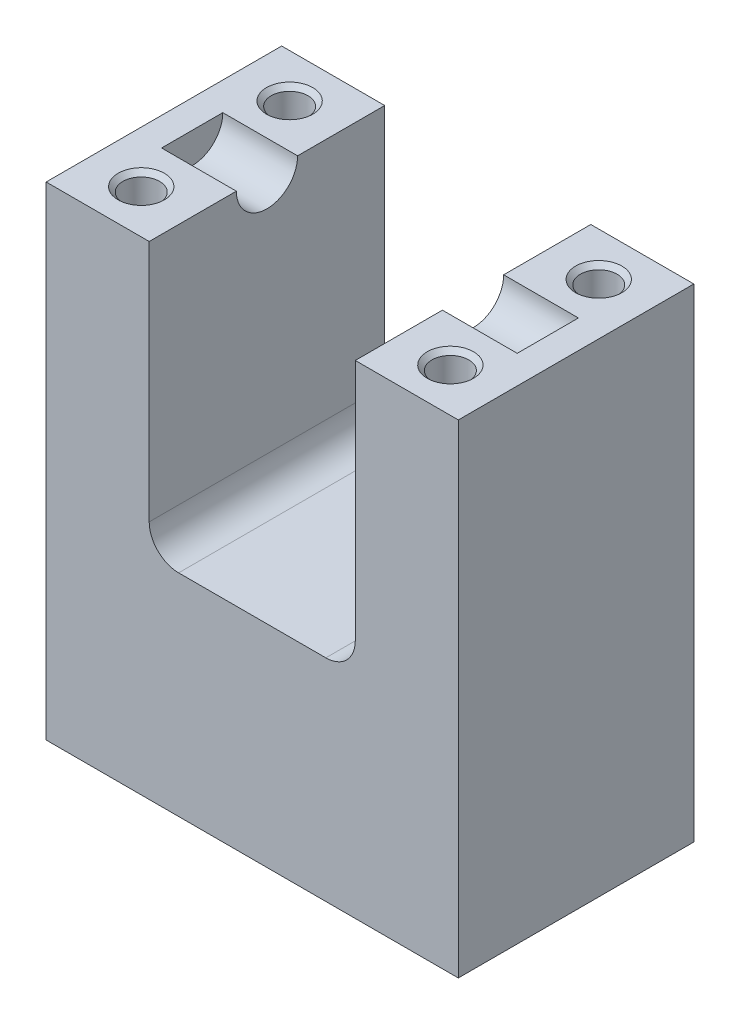
SolidWorks part; units mm, degrees
ref_plane "Front Plane" through (0, 0, 0) normal (0, 0, 1) x (1, 0, 0)
ref_plane "Top Plane" through (0, 0, 0) normal (0, 1, 0) x (1, 0, 0)
ref_plane "Right Plane" through (0, 0, 0) normal (1, 0, 0) x (0, 0, -1)
sketch "Sketch1" plane through (0, 0, 0) normal (0, 1, 0) x (1, 0, 0)
  line L0 (0, 0) -> (44.45, 0)
  line L1 (44.45, 0) -> (44.45, 25.4)
  line L2 (44.45, 25.4) -> (20.066, 25.4)
  line L3 (20.066, 25.4) -> (20.066, 39.116)
  line L4 (20.066, 39.116) -> (0, 39.116)
  line L5 (0, 39.116) -> (0, 0)
  dimension "D1" = 39.116
  dimension "D2" = 44.45
  dimension "D3" = 20.066
  dimension "D4" = 25.4
extrude "L-Base" add sketch "Sketch1" along normal blind 12.7
sketch "Sketch3" plane through (0, 12.7, 0) normal (0, 1, 0) x (1, 0, 0)
  line L1 (0, 0) -> (44.45, 0)
  line L2 (0, 0) -> (0, 25.4)
  line L3 (0, 25.4) -> (44.45, 25.4)
  line L4 (44.45, 0) -> (44.45, 25.4)
  line L5 (0, 0) -> (44.45, 25.4) construction
  line L6 (0, 25.4) -> (44.45, 0) construction
  point P5 (22.225, 12.7)
extrude "Rectangular Extrude" add sketch "Sketch3" along normal offset from surface (10.5664 mm away) 23.2664 up to face at (21.5053, 0, -21.5053)
sketch "Sketch4" plane through (0, 23.2664, 0) normal (0, 1, 0) x (1, 0, 0)
  line L0 (20.066, 25.4) -> (0, 25.4) construction
  line L1 (0, 0) -> (11.1125, 0)
  line L2 (0, 0) -> (0, 25.4)
  line L3 (0, 25.4) -> (11.1125, 25.4)
  line L4 (11.1125, 0) -> (11.1125, 25.4)
  line L5 (0, 0) -> (11.1125, 25.4) construction
  line L6 (0, 25.4) -> (11.1125, 0) construction
  line L7 (44.45, 25.4) -> (0, 25.4) construction
  line L8 (44.45, 0) -> (33.3375, 0)
  line L9 (44.45, 0) -> (44.45, 25.4)
  line L10 (44.45, 25.4) -> (33.3375, 25.4)
  line L11 (33.3375, 0) -> (33.3375, 25.4)
  line L12 (44.45, 0) -> (33.3375, 25.4) construction
  line L13 (44.45, 25.4) -> (33.3375, 0) construction
  line L14 (22.225, 0) -> (22.225, 25.4) construction
  line L15 (0, 0) -> (44.45, 0) construction
  point P4 (5.5563, 12.7)
  point P12 (38.8937, 12.7)
  dimension "D1" = 11.1125
  dimension "D2" = 11.1125
extrude "Fork Extrude" add sketch "Sketch4" along normal blind 29.3624
sketch "Sketch6" plane through (0, 52.6288, 0) normal (0, 1, 0) x (1, 0, 0)
  line L0 (0, 12.7) -> (44.45, 12.7) construction
  line L1 (0, 25.4) -> (0, 0) construction
  line L2 (44.45, 0) -> (44.45, 25.4) construction
  line L3 (11.1125, 0) -> (11.1125, 25.4) construction
  line L4 (3.048, 12.7) -> (41.402, 12.7)
  line L5 (3.048, 12.7) -> (3.048, 9.398)
  line L6 (3.048, 9.398) -> (41.402, 9.398)
  line L7 (41.402, 12.7) -> (41.402, 9.398)
  line L8 (3.048, 12.7) -> (41.402, 9.398) construction
  line L9 (3.048, 9.398) -> (41.402, 12.7) construction
  line L10 (0, 0) -> (44.45, 0) construction
  line L11 (0, 0) -> (0, 25.4) construction
  line L12 (0, 25.4) -> (44.45, 25.4) construction
  line L13 (44.45, 0) -> (44.45, 25.4) construction
  line L14 (0, 0) -> (44.45, 25.4) construction
  line L15 (0, 25.4) -> (44.45, 0) construction
  point P10 (22.225, 12.7)
  dimension "D1" = 3.302
  dimension "D2" = 38.354
  dimension "D3" = 8.0645
revolve "Shaft Recess" cut sketch "Sketch6" angle 360 about L0
hole_wizard "#4 Expansion Insert Recesses #1" positions "Sketch8" profile "Sketch7" counterbore size "#4" standard "ANSI Inch"
sketch "Sketch8" plane through (0, 52.6288, 0) normal (0, 1, 0) x (1, 0, 0)
  line L0 (5.5562, 25.4) -> (5.5562, 0) construction
  line L1 (11.1125, 25.4) -> (0, 25.4) construction
  line L2 (0, 0) -> (11.1125, 0) construction
  line L4 (38.8937, 25.4) -> (38.8937, 0) construction
  line L5 (44.45, 25.4) -> (33.3375, 25.4) construction
  line L6 (33.3375, 0) -> (44.45, 0) construction
  line L8 (11.1125, 20.701) -> (0, 20.701) construction
  line L9 (11.1125, 16.002) -> (11.1125, 25.4) construction
  line L10 (0, 25.4) -> (0, 0) construction
  line L12 (11.1125, 4.699) -> (0, 4.699) construction
  line L13 (11.1125, 0) -> (11.1125, 9.398) construction
  line L15 (33.3375, 20.701) -> (44.45, 20.701) construction
  line L16 (33.3375, 25.4) -> (33.3375, 16.002) construction
  line L17 (44.45, 0) -> (44.45, 25.4) construction
  line L19 (33.3375, 4.699) -> (44.45, 4.699) construction
  line L20 (33.3375, 25.4) -> (33.3375, 0) construction
  point P0 (5.5562, 20.701)
  point P2 (5.5563, 4.699)
  point P4 (38.8937, 20.701)
  point P6 (38.8937, 4.699)
  dimension "D1" = 16.002
sketch "Sketch7" plane through (5.5562, 52.6288, -20.701) normal (1, 0, 0) x (0, 0, 1)
  line L0 (0, 0) -> (0, 13.6806)
  line L1 (0, 13.6806) -> (1.6319, 12.7)
  line L2 (1.6319, 12.7) -> (1.6319, 4.7625)
  line L3 (1.6319, 4.7625) -> (1.9844, 4.7625)
  line L4 (1.9844, 4.7625) -> (1.9844, 0)
  line L5 (1.9844, 0) -> (0, 0)
  line L10 (0, 13.6806) -> (-1.632, 12.7) construction
  line L11 (0, -6.35) -> (0, 107.95) construction
  dimension "Hole Dia." = 3.2639
  dimension "Hole Depth" = 12.7
  dimension "C'Bore Dia." = 3.9688
  dimension "C'Bore Depth" = 4.7625
  dimension "Drill Angle" = 118
hole_wizard "#4 Expansion Insert Recesses #2" positions "Sketch11" profile "Sketch10" counterbore size "#4" standard "ANSI Inch"
sketch "Sketch11" plane through (0, 0, 0) normal (0, -1, 0) x (-1, 0, 0)
  line L0 (0, 39.116) -> (0, 0) construction
  line L1 (0, 0) -> (-44.45, 0) construction
  point P0 (-10.033, 10.033)
  point P2 (-28.956, 10.033)
  point P4 (-10.033, 28.956)
  dimension "D1" = 10.033
  dimension "D2" = 10.033
  dimension "D3" = 18.923
  dimension "D4" = 18.923
sketch "Sketch10" plane through (10.033, 0, -10.033) normal (1, 0, 0) x (0, 0, -1)
  line L0 (0, 0) -> (0, 10.5056)
  line L1 (0, 10.5056) -> (1.6319, 9.525)
  line L2 (1.6319, 9.525) -> (1.6319, 4.7625)
  line L3 (1.6319, 4.7625) -> (1.9844, 4.7625)
  line L4 (1.9844, 4.7625) -> (1.9844, 0)
  line L5 (1.9844, 0) -> (0, 0)
  line L10 (0, 10.5056) -> (-1.632, 9.525) construction
  line L11 (0, -6.35) -> (0, 107.95) construction
  dimension "Hole Dia." = 3.2639
  dimension "Hole Depth" = 9.525
  dimension "C'Bore Dia." = 3.9688
  dimension "C'Bore Depth" = 4.7625
  dimension "Drill Angle" = 118
fillet "L-Base Fillet" radius 6.35 3 edges at (10.033, 12.7, -39.116)
fillet "Fork Fillet" radius 3.175 2 edges at (33.3375, 23.2664, -12.7)
chamfer "Installation Chamfers #1" distance 0.508 angle 45 4 edges at (38.8937, 52.6288, -18.7166) (38.8937, 52.6288, -2.7146) (5.5563, 52.6288, -2.7146) (5.5562, 52.6288, -18.7166)
chamfer "Installation Chamfers #2" distance 0.508 angle 45 3 edges at (10.033, 0, -30.9404) (10.033, 0, -12.0174) (28.956, 0, -12.0174)
chamfer "Print Bed Chamfer" distance 0.508 angle 45 7 edges at (0, 0, -19.558) (10.033, 0, -39.116) (20.066, 0, -35.433) (35.433, 0, -25.4) (44.45, 0, -12.7) (22.225, 0, 0) (21.9259, 0, -27.2599)
